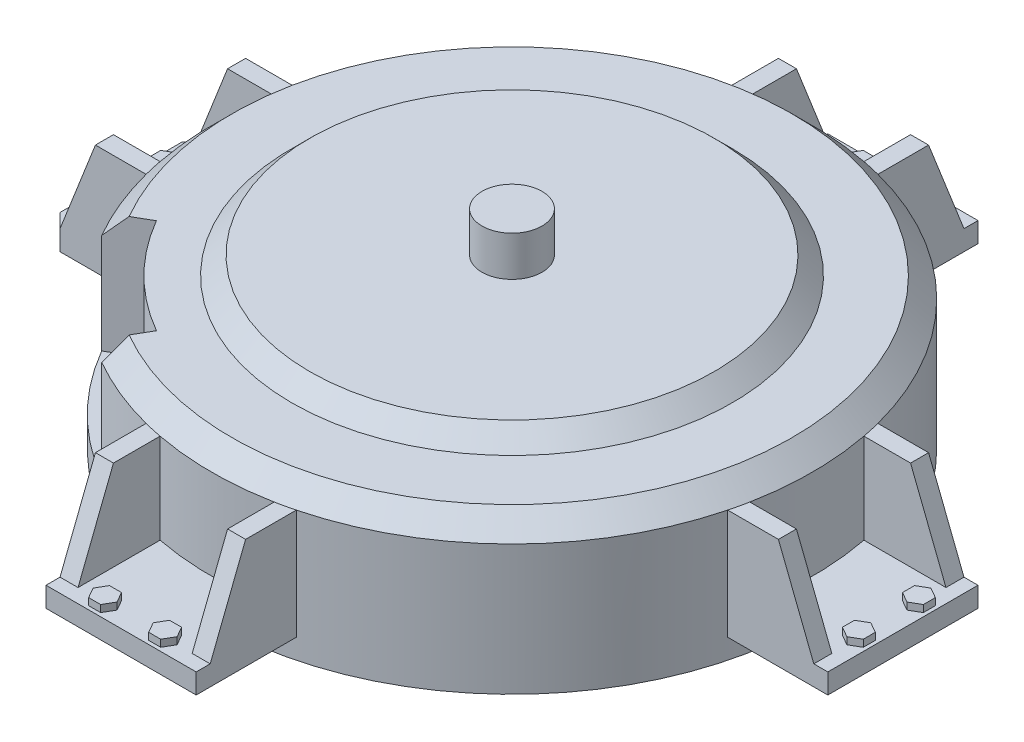
SolidWorks part; units mm, degrees
material "6061-T6 (SS)"
ref_plane "Front Plane" through (0, 0, 0) normal (0, 0, 1) x (1, 0, 0)
ref_plane "Top Plane" through (0, 0, 0) normal (0, 1, 0) x (1, 0, 0)
ref_plane "Right Plane" through (0, 0, 0) normal (1, 0, 0) x (0, 0, -1)
sketch "Sketch1" plane through (0, 0, 0) normal (0, 1, 0) x (1, 0, 0)
  circle A0 centre (0, 0) radius 150
  dimension "D1" = 300
extrude "Boss-Extrude1" add sketch "Sketch1" along normal blind 75
chamfer "Chamfer1" distance 10 angle 45 1 edges at (0, 75, 150)
sketch "Sketch2" plane through (0, 75, 0) normal (0, 1, 0) x (1, 0, 0)
  line L0 (0, 0) -> (-227.2312, 0) construction
  line L1 (-145.2369, 37.5) -> (-195.2369, 37.5)
  line L2 (-195.2369, 37.5) -> (-195.2369, -37.5)
  line L3 (-195.2369, -37.5) -> (-145.2369, -37.5)
  circle A0 centre (0, 0) radius 150 construction
  arc A1 (-145.2369, 37.5) -> (-145.2369, -37.5) centre (0, 0) ccw
  dimension "D1" = 75
  dimension "D2" = 50
extrude "Boss-Extrude2" add sketch "Sketch2" along normal blind 10 from offset 65 offset against normal yes
chamfer "Chamfer2" distance 7 angle 45 2 edges at (-195.2369, 15, -37.5) (-195.2369, 15, 37.5)
sketch "Sketch3" plane through (0, 0, 37.5) normal (0, 0, 1) x (1, 0, 0)
  line L0 (-145.2369, 20) -> (-145.2369, 65)
  line L1 (-150, 65) -> (150, 65) construction
  line L2 (-145.2369, 65) -> (-170.5569, 65)
  line L3 (-170.5569, 65) -> (-188.2369, 20)
  line L4 (-188.2369, 20) -> (-145.2369, 20)
  dimension "D1" = 17.68
extrude "Boss-Extrude3" add sketch "Sketch3" against normal blind 9
sketch "Sketch4" plane through (0, 20, 0) normal (0, 1, 0) x (1, 0, 0)
  line L0 (-149.929, 4.6131) -> (-235.1153, 4.6131) construction
  line L1 (-188.2369, 37.5) -> (-188.2369, -37.5) construction
  line L3 (-183.0407, -12) -> (-188.2369, -9)
  line L4 (-188.2369, -9) -> (-193.433, -12)
  line L5 (-193.433, -12) -> (-193.433, -18)
  line L6 (-193.433, -18) -> (-188.2369, -21)
  line L7 (-188.2369, -21) -> (-183.0407, -18)
  line L8 (-183.0407, -18) -> (-183.0407, -12)
  arc A0 (-145.2369, 37.5) -> (-147.2676, -28.5) centre (0, 0) ccw construction
  circle A1 centre (-188.2369, -15) radius 5.1962 construction
  dimension "D1" = 6
  dimension "D2" = 13.5
extrude "Boss-Extrude4" add sketch "Sketch4" along normal blind 3.5
mirror "Mirror1" about plane through (0, 0, 0) normal (0, 0, 1) of "Boss-Extrude3", "Boss-Extrude4"
pattern_circular "CirPattern1" count 4 over 360 about axis through (0, 0, 0) along (0, 1, 0) of "Mirror1", "Boss-Extrude2", "Boss-Extrude3", "Boss-Extrude4"
sketch "Sketch5" plane through (0, 75, 0) normal (0, 1, 0) x (1, 0, 0)
  line L0 (0, 167.8214) -> (0, -215.4744) construction
  line L1 (322.1757, 0) -> (-317.514, 0) construction
  line L2 (-112.5833, -65) -> (-129.9038, -75)
  line L3 (-65, -112.5833) -> (-75, -129.9038)
  arc A3 (-112.5833, -65) -> (-65, -112.5833) centre (0, 0) ccw
  arc A21 (-147.2676, -28.5) -> (-145.2369, -37.5) centre (0, 0) ccw
  arc A22 (-145.2369, -37.5) -> (-37.5, -145.2369) centre (0, 0) ccw
  arc A23 (-37.5, -145.2369) -> (-28.5, -147.2676) centre (0, 0) ccw
  arc A24 (-28.5, -147.2676) -> (28.5, -147.2676) centre (0, 0) ccw
  arc A25 (28.5, -147.2676) -> (37.5, -145.2369) centre (0, 0) ccw
  arc A26 (37.5, -145.2369) -> (145.2369, -37.5) centre (0, 0) ccw
  arc A27 (145.2369, -37.5) -> (147.2676, -28.5) centre (0, 0) ccw
  arc A28 (147.2676, -28.5) -> (147.2676, 28.5) centre (0, 0) ccw
  arc A29 (147.2676, 28.5) -> (145.2369, 37.5) centre (0, 0) ccw
  arc A30 (145.2369, 37.5) -> (37.5, 145.2369) centre (0, 0) ccw
  arc A31 (37.5, 145.2369) -> (28.5, 147.2676) centre (0, 0) ccw
  arc A32 (28.5, 147.2676) -> (-28.5, 147.2676) centre (0, 0) ccw
  arc A33 (-28.5, 147.2676) -> (-37.5, 145.2369) centre (0, 0) ccw
  arc A34 (-37.5, 145.2369) -> (-145.2369, 37.5) centre (0, 0) ccw
  arc A35 (-145.2369, 37.5) -> (-147.2676, 28.5) centre (0, 0) ccw
  arc A36 (-147.2676, 28.5) -> (-147.2676, -28.5) centre (0, 0) ccw
  arc A38 (-129.9038, -75) -> (-75, -129.9038) centre (0, 0) ccw
  dimension "D1" = 0
  dimension "D2" = 30
  dimension "D3" = 30
extrude "Cut-Extrude1" cut sketch "Sketch5" against normal blind 60
sketch "Sketch6" plane through (0, 75, 0) normal (0, 1, 0) x (1, 0, 0)
  circle A0 centre (0, 0) radius 110
  dimension "D1" = 220
extrude "Boss-Extrude5" add sketch "Sketch6" along normal blind 9 draft 45
sketch "Sketch7" plane through (0, 84, 0) normal (0, 1, 0) x (1, 0, 0)
  circle A0 centre (0, 0) radius 15
  dimension "D1" = 30
extrude "Boss-Extrude6" add sketch "Sketch7" along normal blind 20
pattern_circular "CirPattern3" [suppressed] count 4 over 360
sketch "Croquis1" plane through (0, 75, 0) normal (0, 1, 0) x (1, 0, 0)
  point P0 (0, 0)
